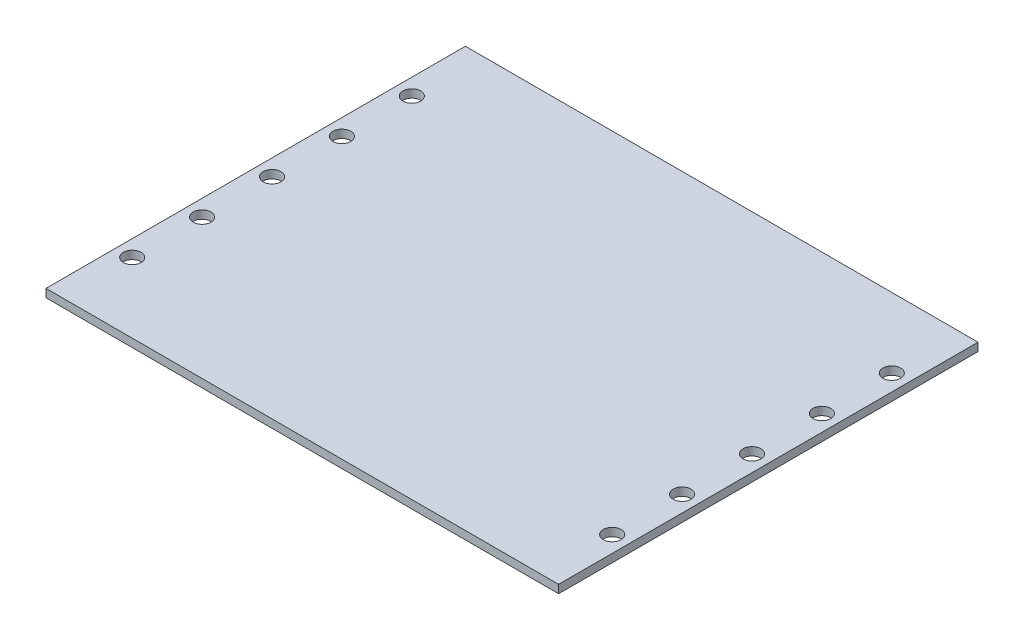
SolidWorks part; units mm, degrees
ref_plane "Front Plane" through (0, 0, 0) normal (0, 0, 1) x (1, 0, 0)
ref_plane "Top Plane" through (0, 0, 0) normal (0, 1, 0) x (1, 0, 0)
ref_plane "Right Plane" through (0, 0, 0) normal (1, 0, 0) x (0, 0, -1)
sketch "Sketch1" plane through (0, 0, 0) normal (0, 1, 0) x (1, 0, 0)
  line L2 (0, 0) -> (110, 0)
  line L5 (0, 90) -> (110, 90) construction
  line L7 (0, 0) -> (110, 0) construction
  line L8 (110, 90) -> (110, 0) construction
  line L12 (110, 0) -> (110, 90)
  line L13 (110, 90) -> (0, 90)
  line L14 (0, 90) -> (0, 0)
extrude "FR4" add sketch "Sketch1" along normal blind 1.7526
ref_plane "center-of-slot" through (0, 0.8763, 0) normal (0, -1, 0) x (-1, 0, 0)
sketch "Sketch7" plane through (0, 1.7526, 0) normal (0, 1, 0) x (1, 0, 0)
  circle A0 centre (3.5, 15) radius 1.905
  circle A1 centre (106.5, 15) radius 1.905
  circle A2 centre (106.5, 30) radius 1.905
  circle A3 centre (106.5, 45) radius 1.905
  circle A4 centre (106.5, 60) radius 1.905
  circle A5 centre (106.5, 75) radius 1.905
  circle A6 centre (3.5, 30) radius 1.905
  circle A7 centre (3.5, 45) radius 1.905
  circle A8 centre (3.5, 60) radius 1.905
  circle A9 centre (3.5, 75) radius 1.905
  dimension "D1" = 2
  dimension "D2" = 5
extrude "Cut-Extrude1" cut sketch "Sketch7" against normal through all
